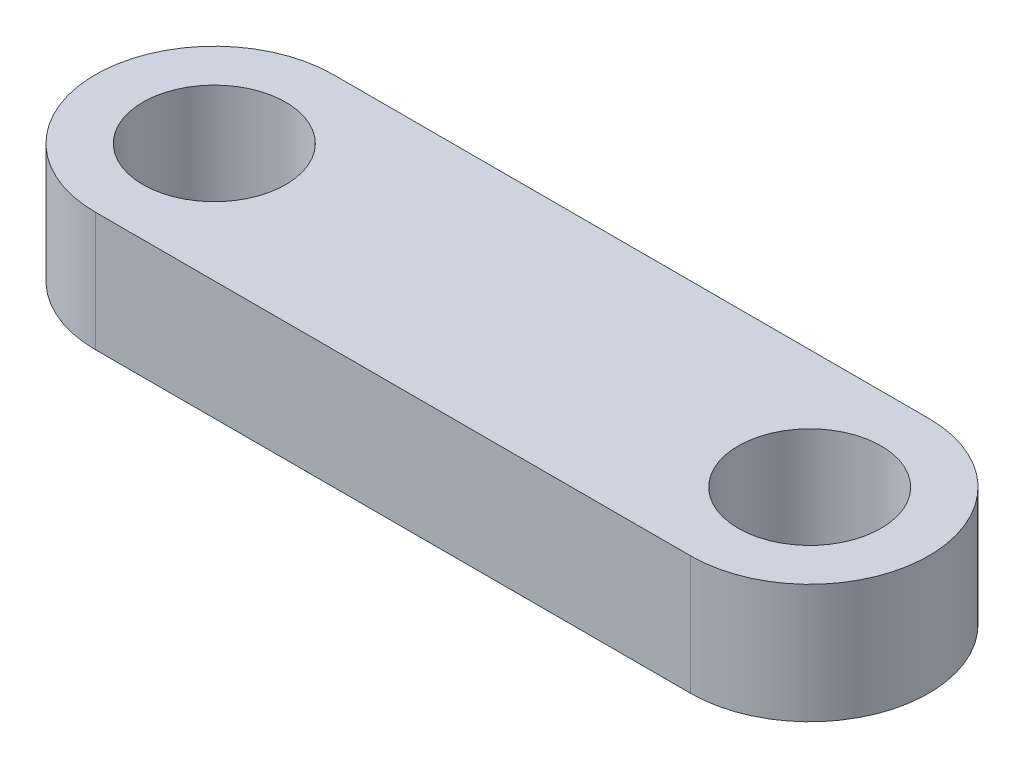
SolidWorks part; units mm, degrees
ref_plane "Front Plane" through (0, 0, 0) normal (0, 0, 1) x (1, 0, 0)
ref_plane "Top Plane" through (0, 0, 0) normal (0, 1, 0) x (1, 0, 0)
ref_plane "Right Plane" through (0, 0, 0) normal (1, 0, 0) x (0, 0, -1)
sketch "Sketch1" plane through (0, 0, 0) normal (0, 1, 0) x (1, 0, 0)
  line L0 (-55, 0) -> (55, 0) construction
  line L1 (-13.3522, 2.54) -> (-0.6522, 2.54)
  line L2 (-13.3522, -2.54) -> (-0.6522, -2.54)
  circle A0 centre (-13.3522, 0) radius 1.524
  circle A1 centre (-0.6522, 0) radius 1.524
  arc A2 (-13.3522, 2.54) -> (-13.3522, -2.54) centre (-13.3522, 0) ccw
  arc A3 (-0.6522, -2.54) -> (-0.6522, 2.54) centre (-0.6522, 0) ccw
  dimension "D1" = 3.048
  dimension "D3" = 5.08
  dimension "D2" = 12.7
extrude "Boss-Extrude1" add sketch "Sketch1" along normal blind 2.54
